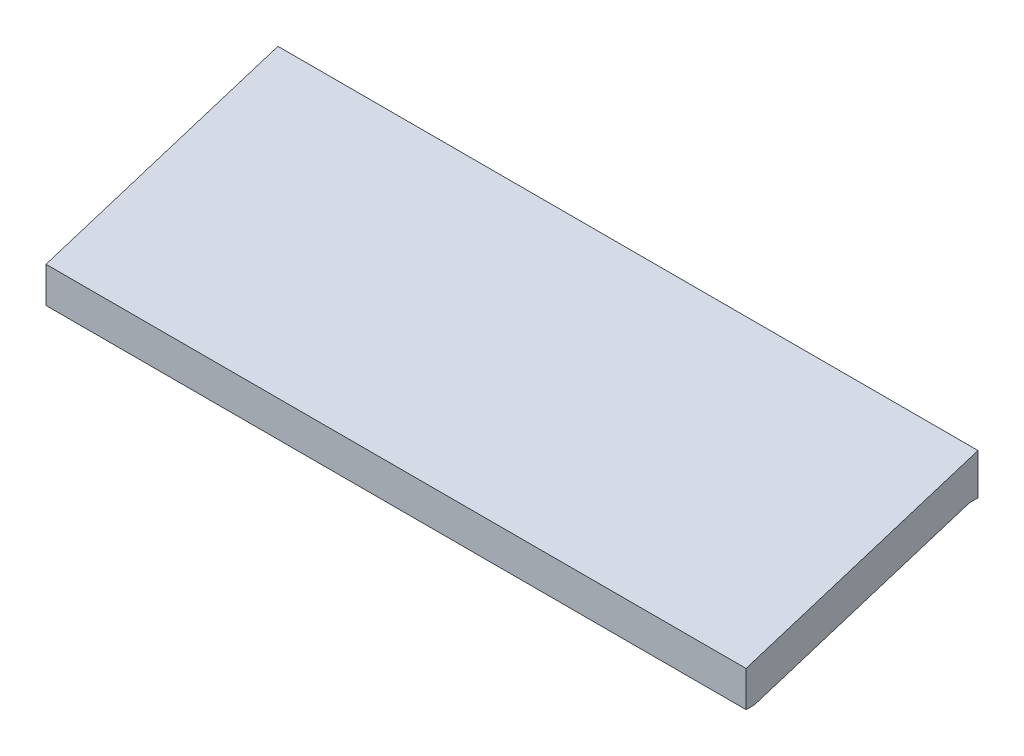
SolidWorks part; units mm, degrees
ref_plane "Front" through (0, 0, 0) normal (0, 0, 1) x (1, 0, 0)
ref_plane "Top" through (0, 0, 0) normal (0, 1, 0) x (1, 0, 0)
ref_plane "Right" through (0, 0, 0) normal (1, 0, 0) x (0, 0, -1)
sketch "Sketch2" plane through (0, 0, 0) normal (1, 0, 0) x (0, 0, -1)
  line L0 (51, -1.7379) -> (0, -17.7379)
  line L1 (-2, -17.7379) -> (-2, -24.7379)
  line L2 (0, -17.7379) -> (0, -22.7379)
  line L3 (53, -1.7379) -> (53, 0.9857)
  line L4 (51, -1.7379) -> (51, -8.7379)
  line L5 (0, -17.7379) -> (51, -1.7379)
  line L6 (-2, -24.7379) -> (0, -24.7379)
  line L7 (53, -1.7379) -> (53, -8.7379)
  line L8 (50.4013, 0.1704) -> (-0.5987, -15.8296)
  line L9 (-2, -17.7379) -> (-2, -16.2692)
  line L10 (-0.5987, -15.8296) -> (-2, -16.2692)
  line L11 (0, -22.7379) -> (0, -24.7379)
  line L14 (50.4013, 0.1704) -> (53, 0.9857)
  line L15 (-2, -24.7379) -> (53, -24.7379) construction
  line L16 (0, -22.7379) -> (51, -22.7379) construction
  line L17 (51, -8.7379) -> (53, -8.7379)
  line L19 (53, -1.7379) -> (53, -24.7379) construction
  line L20 (51, -1.7379) -> (51, -22.7379) construction
  dimension "D2" = 5
  dimension "D5" = 7
  dimension "D4" = 2
extrude "Boss-Extrude2" add sketch "Sketch2" along normal blind 166 contours L4 L17 L7 L3 L14 L8 L10 L9 L1 L6 L11 L2 L0
sketch "Sketch3" plane through (0, 0, 0) normal (-1, 0, 0) x (0, 0, 1)
  line L0 (-51, -1.7379) -> (0, -17.7379)
  line L1 (0, -17.7379) -> (0, -24.7379)
  line L2 (0, -24.7379) -> (-51, -8.7379)
  line L3 (-51, -8.7379) -> (-51, -1.7379)
extrude "Boss-Extrude3" add sketch "Sketch3" against normal blind 2
sketch "Sketch4" plane through (166, 0, 0) normal (1, 0, 0) x (0, 0, -1)
  line L0 (51, -1.7379) -> (0, -17.7379)
  line L1 (0, -17.7379) -> (0, -24.7379)
  line L2 (0, -24.7379) -> (51, -8.7379)
  line L3 (51, -1.7379) -> (51, -8.7379) construction
  line L4 (51, -8.7379) -> (51, -1.7379)
extrude "Boss-Extrude4" add sketch "Sketch4" against normal blind 2
